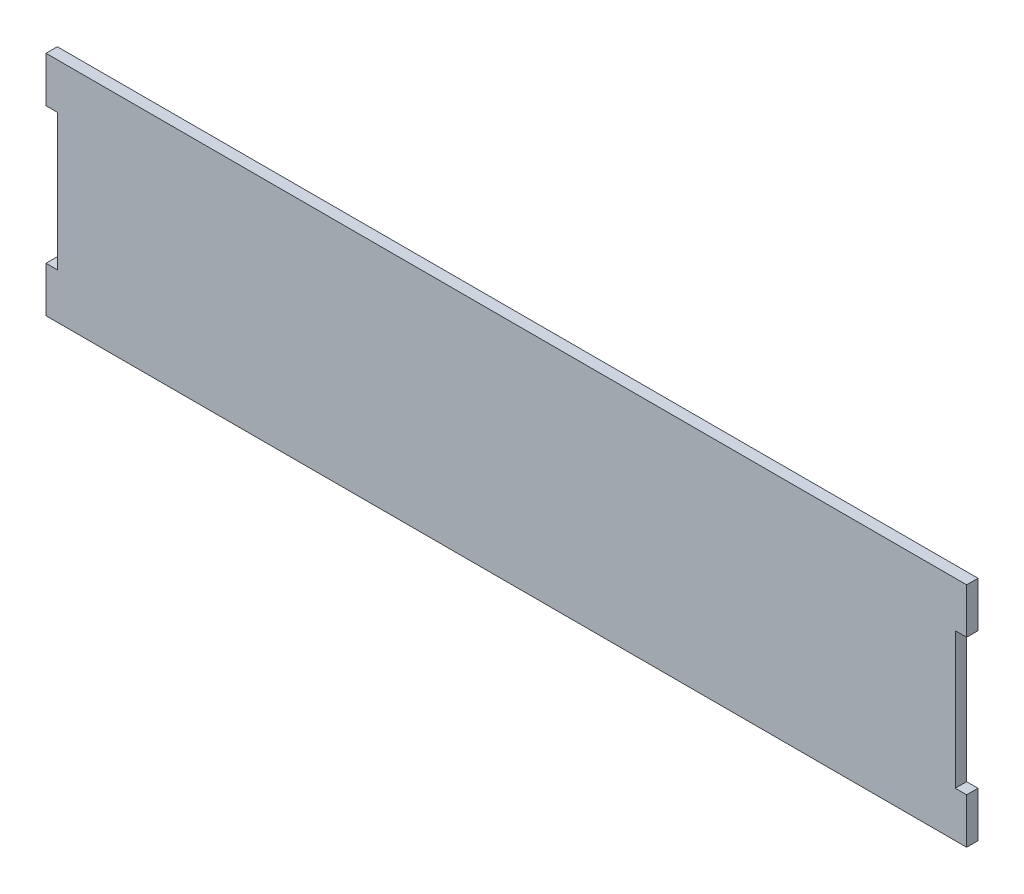
SolidWorks part; units mm, degrees
ref_plane "Front Plane" through (0, 0, 0) normal (0, 0, 1) x (1, 0, 0)
ref_plane "Top Plane" through (0, 0, 0) normal (0, 1, 0) x (1, 0, 0)
ref_plane "Right Plane" through (0, 0, 0) normal (1, 0, 0) x (0, 0, -1)
sketch "Sketch1" plane through (0, 0, 0) normal (0, 0, 1) x (1, 0, 0)
  line L1 (0, 0) -> (-405, 0)
  line L2 (0, 0) -> (0, -100)
  line L3 (0, -100) -> (-405, -100)
  line L4 (-405, 0) -> (-405, -100)
  dimension "D1" = 100
  dimension "D2" = 405
extrude "Boss-Extrude1" add sketch "Sketch1" along normal blind 5
sketch "Sketch2" plane through (0, 0, 5) normal (0, 0, 1) x (1, 0, 0)
  line L0 (-405, 0) -> (-405, -100) construction
  line L1 (-405, -75) -> (-400, -75)
  line L2 (-405, -75) -> (-405, -80)
  line L3 (-405, -80) -> (-400, -80)
  line L4 (-400, -75) -> (-400, -80)
  line L5 (-405, -100) -> (0, -100) construction
  line L6 (-405, -50) -> (-389.3855, -50) construction
  line L7 (-405, -25) -> (-405, -20)
  line L8 (-405, -25) -> (-400, -25)
  line L9 (-400, -25) -> (-400, -20)
  line L10 (-405, -20) -> (-400, -20)
  line L11 (-202.5, 0) -> (-202.5, -31.4522) construction
  line L12 (0, 0) -> (-405, 0) construction
  line L13 (0, -50) -> (-15.6145, -50) construction
  line L14 (0, -20) -> (-5, -20)
  line L15 (-5, -25) -> (-5, -20)
  line L16 (0, -25) -> (-5, -25)
  line L17 (0, -25) -> (0, -20)
  line L18 (-5, -75) -> (-5, -80)
  line L19 (0, -80) -> (-5, -80)
  line L20 (0, -75) -> (0, -80)
  line L21 (0, -75) -> (-5, -75)
  dimension "D1" = 5
  dimension "D2" = 5
  dimension "D3" = 20
extrude "Cut-Extrude1" cut sketch "Sketch2" against normal blind 5
sketch "Sketch3" plane through (0, 0, 5) normal (0, 0, 1) x (1, 0, 0)
  line L0 (-400, -75) -> (-405, -75) construction
  line L1 (-405, -25) -> (-415, -25)
  line L2 (-405, -25) -> (-405, -75)
  line L3 (-405, -75) -> (-415, -75)
  line L4 (-415, -25) -> (-415, -75)
  line L5 (-405, -30) -> (-410, -30)
  line L6 (-405, -30) -> (-405, -70)
  line L7 (-405, -70) -> (-410, -70)
  line L8 (-410, -30) -> (-410, -70)
  line L9 (-202.5, 0) -> (-202.5, -61.3088) construction
  line L10 (0, 0) -> (-405, 0) construction
  line L11 (5, -30) -> (5, -70)
  line L12 (0, -70) -> (5, -70)
  line L13 (0, -30) -> (0, -70)
  line L14 (0, -30) -> (5, -30)
  line L15 (10, -25) -> (10, -75)
  line L16 (0, -75) -> (10, -75)
  line L17 (0, -25) -> (0, -75)
  line L18 (0, -25) -> (10, -25)
  line M8 (0, -75) -> (0, -25)
  line M18 (-405, -25) -> (-405, -75)
  dimension "D1" = 10
  dimension "D2" = 5
  dimension "D3" = 5
  dimension "D4" = 5
extrude "Boss-Extrude2" add sketch "Sketch3" against normal blind 5 contours L8 L5 L1 L4 L3 L7 M18 | L18 L14 L11 L12 L16 L15 M8
sketch "Sketch4" plane through (0, 0, 5) normal (0, 0, 1) x (1, 0, 0)
  line L0 (-405, -100) -> (0, -100) construction
  line L1 (0, -100) -> (0, -80) construction
  circle A0 centre (-50, -50) radius 16
  dimension "D1" = 32
  dimension "D2" = 50
  dimension "D3" = 50
extrude "Cut-Extrude2" [suppressed] cut sketch "Sketch4" against normal blind 5
sketch "Sketch5" plane through (0, 0, 5) normal (0, 0, 1) x (1, 0, 0)
  line L0 (0, 0) -> (-405, 0) construction
  line L1 (-344, -63) -> (-366, -63)
  line L2 (-344, -63) -> (-344, -37)
  line L3 (-344, -37) -> (-366, -37)
  line L4 (-366, -63) -> (-366, -37)
  line L5 (-405, -80) -> (-405, -100) construction
  line L6 (-314, -63) -> (-314, -37)
  line L7 (-314, -63) -> (-336, -63)
  line L8 (-336, -63) -> (-336, -37)
  line L9 (-314, -37) -> (-336, -37)
  point P4 (-344, -50)
  point P7 (-355, -63)
  dimension "D1" = 26
  dimension "D2" = 22
  dimension "D3" = 50
  dimension "D4" = 50
  dimension "D5" = 2
extrude "Cut-Extrude3" [suppressed] cut sketch "Sketch5" against normal blind 5 contours L2 L1 L4 L3 | L6 L9 L8 L7
sketch "Sketch6" plane through (0, 0, 5) normal (0, 0, 1) x (1, 0, 0)
  line L0 (-202.5, 0) -> (-202.5, -44.5474) construction
  line L1 (-5, -25) -> (10, -25)
  line L2 (-5, -25) -> (-5, -75)
  line L3 (-5, -75) -> (10, -75)
  line L4 (10, -25) -> (10, -75)
  line L5 (0, 0) -> (-405, 0) construction
  line L6 (-415, -25) -> (-415, -75)
  line L7 (-400, -75) -> (-415, -75)
  line L8 (-400, -25) -> (-400, -75)
  line L9 (-400, -25) -> (-415, -25)
extrude "Cut-Extrude4" cut sketch "Sketch6" against normal blind 5
